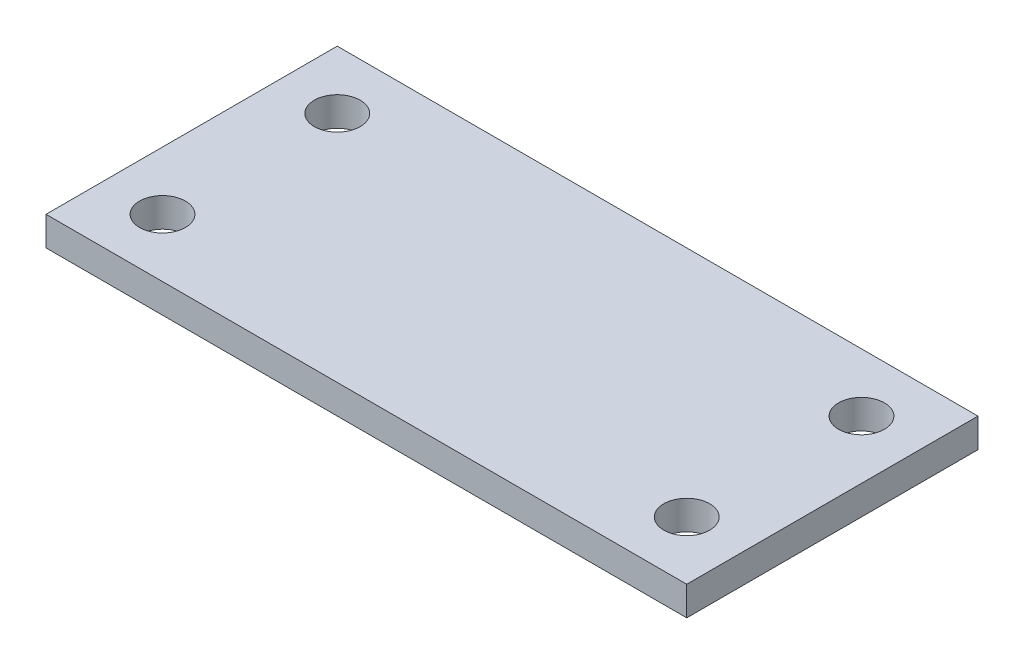
SolidWorks part; units mm, degrees
ref_plane "Front Plane" through (0, 0, 0) normal (0, 0, 1) x (1, 0, 0)
ref_plane "Top Plane" through (0, 0, 0) normal (0, 1, 0) x (1, 0, 0)
ref_plane "Right Plane" through (0, 0, 0) normal (1, 0, 0) x (0, 0, -1)
sketch "Sketch1" plane through (0, 0, 0) normal (0, 1, 0) x (1, 0, 0)
  line L0 (-22, 10) -> (22, 10)
  line L1 (-18, 6) -> (18, 6)
  line L2 (-18, 6) -> (-18, -6)
  line L3 (-18, -6) -> (18, -6)
  line L4 (18, 6) -> (18, -6)
  line L5 (-18, 6) -> (18, -6) construction
  line L6 (-18, -6) -> (18, 6) construction
  line L7 (22, 10) -> (22, -10)
  line L8 (-22, -10) -> (22, -10)
  line L9 (-22, 10) -> (-22, -10)
  circle A0 centre (-18, 6) radius 1.575
  circle A1 centre (18, 6) radius 1.575
  circle A2 centre (18, -6) radius 1.575
  circle A3 centre (-18, -6) radius 1.575
  point P0 (0, 0)
  dimension "D3" = 3.15
  dimension "D1" = 36
  dimension "D2" = 12
  dimension "D4" = 4
extrude "Boss-Extrude1" add sketch "Sketch1" along normal blind 2 contours L0 L9 L8 L7 A3 L2 A0 L1 A1 L4 A2 L3 | A3 L3 A2 L4 A1 L1 A0 L2
